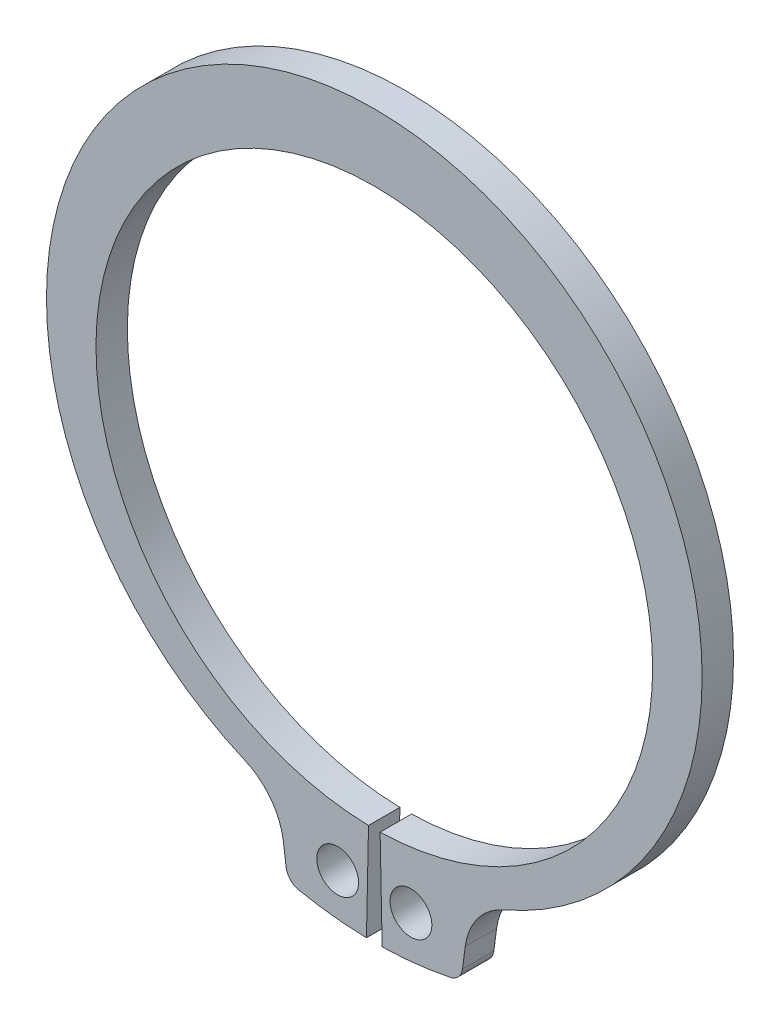
SolidWorks part; units mm, degrees
ref_plane "Plane1" through (0, 0, 0) normal (0, 0, 1) x (1, 0, 0)
ref_plane "Plane2" through (0, 0, 0) normal (0, 1, 0) x (1, 0, 0)
ref_plane "Plane3" through (0, 0, 0) normal (1, 0, 0) x (0, 0, -1)
sketch "Clipboard" plane through (0, 0, 0) normal (0, 0, 1) x (1, 0, 0)
  line L0 (0, 0) -> (3.2, 0)
  line L1 (0, 0) -> (0, 1.6)
  line L2 (0, 0) -> (0, -4.7)
  circle A0 centre (0, 0) radius 1
  circle A1 centre (0, 0) radius 14
  dimension "HoleDia" = 2
  dimension "ShaftDia" = 28
  dimension "LargeSection" = 3.2
  dimension "SmallSection" = 1.6
  dimension "LugSection" = 4.7
sketch "BodySke" plane through (0, 0, 0) normal (0, 0, 1) x (1, 0, 0)
  line L0 (-1.5431, 0) -> (1.5431, 0) construction
  line L1 (0, 0) -> (0, 16.5) construction
  line L2 (0.2771, -13.2971) -> (0.375, -17.9961)
  line L3 (-0.2771, -13.2971) -> (-0.375, -17.9961)
  line L4 (0, 0) -> (7.418, -16.4004) construction
  line L5 (0, 0) -> (-7.418, -16.4004) construction
  line L7 (4.3451, -15.9959) -> (4.2136, -16.9953)
  line L8 (-4.3451, -15.9959) -> (-4.2136, -16.9953)
  circle A0 centre (0, 0) radius 13.3 construction
  arc A1 (0.2771, -13.2971) -> (-0.2771, -13.2971) centre (0, 0) ccw
  arc A2 (6.1405, -13.5759) -> (-6.1405, -13.5759) centre (0, 0.8352) ccw construction
  arc A3 (0.375, -17.9961) -> (3.6208, -17.6321) centre (0, 0) ccw
  arc A4 (6.1927, -13.5535) -> (4.3451, -15.9959) centre (7.418, -16.4004) ccw
  arc A5 (-4.3451, -15.9959) -> (-6.1927, -13.5535) centre (-7.418, -16.4004) ccw
  arc A6 (-3.6208, -17.6321) -> (-0.375, -17.9961) centre (0, 0) ccw
  arc A7 (6.1927, -13.5535) -> (-6.1927, -13.5535) centre (0, 0.8352) ccw
  arc A8 (-4.4268, -15.3754) -> (4.4268, -15.3754) centre (0, 0) ccw construction
  circle A9 centre (1.75, -15.904) radius 1
  circle A10 centre (-1.75, -15.904) radius 1
  arc A11 (4.2136, -16.9953) -> (3.6208, -17.6321) centre (3.47, -16.8974) cw
  arc A12 (-4.2136, -16.9953) -> (-3.6208, -17.6321) centre (-3.47, -16.8974) ccw
  point P28 (4.145, -17.5163)
  point P31 (-4.145, -17.5163)
  dimension "HoleDia" = 2
  dimension "GrooveDia" = 26.6
  dimension "LugRad" = 18
  dimension "HoleOffsetRad" = 16
  dimension "D3" = 0.75
  dimension "LargeRad" = 16.5
  dimension "SmallRad" = 14.9
  dimension "SmallAngle" = 48.675
  dimension "D2" = 15
  dimension "HoleSpacing" = 3.5
  dimension "Gap" = 0.75
extrude "Body" add sketch "BodySke" against normal blind 1.5
sketch "NotSke" plane through (0, 0, 0) normal (0, 0, 1) x (1, 0, 0)
  line L0 (1.75, -14.904) -> (1.75, -16.904)
  line L1 (1.75, -16.904) -> (-1.75, -16.904)
  line L2 (-1.75, -16.904) -> (-1.75, -14.904)
  line L3 (-1.75, -14.904) -> (1.75, -14.904)
  circle A0 centre (1.75, -15.904) radius 1 construction
  circle A1 centre (-1.75, -15.904) radius 1 construction
extrude "Notch" [suppressed] cut sketch "NotSke" against normal through all
sketch "UnlSke" plane through (0, 0, 0) normal (0, 0, 1) x (1, 0, 0)
  line L0 (-3.0832, -17.734) -> (-2.2781, -13.1034)
  line L1 (3.0832, -17.734) -> (2.2781, -13.1034)
  arc A0 (2.2781, -13.1034) -> (-2.2781, -13.1034) centre (0, 0) ccw
  arc A1 (3.0832, -17.734) -> (-3.0832, -17.734) centre (0, 0) ccw
  arc A2 (0.375, -17.9961) -> (3.6208, -17.6321) centre (0, 0) ccw construction
  arc A3 (0.2771, -13.2971) -> (-0.2771, -13.2971) centre (0, 0) ccw construction
  circle A4 centre (-1.75, -15.904) radius 1 construction
  circle A5 centre (1.75, -15.904) radius 1 construction
extrude "Unlug" [suppressed] add sketch "UnlSke" against normal through all
equation "' \"ShaftDia@Clipboard\" = 3"
equation "' \"Thickness@Body\" = 0.4"
equation "' \"GrooveDia@BodySke\" = 2.8"
equation "' \"LugSection@Clipboard\" = 1.9"
equation "' \"LargeSection@Clipboard\" = 0.8"
equation "' \"HoleDia@Clipboard\" = 1.0"
equation "' \"ShaftDia@Clipboard\" = 10"
equation "' \"Thickness@Body\" = 1.0"
equation "' \"GrooveDia@BodySke\" = 9.6"
equation "' \"LugSection@Clipboard\" = 3.3"
equation "' \"LargeSection@Clipboard\" = 1.8"
equation "' \"HoleDia@Clipboard\" = 1.5"
equation "\"SmallSection@Clipboard\" = \"LargeSection@Clipboard\" * 0.5"
equation "\"Gap@BodySke\" =  \"Thickness@Body\" / 2"
equation "\"LargeRad@BodySke\" =  \"GrooveDia@BodySke\" / 2 +  \"LargeSection@Clipboard\""
equation "\"SmallRad@BodySke\" =  \"GrooveDia@BodySke\" / 2 +  \"SmallSection@Clipboard\""
equation "\"LugRad@BodySke\" = \"GrooveDia@BodySke\" / 2 + \"LugSection@Clipboard\""
equation "\"HoleOffsetRad@BodySke\" = (  \"ShaftDia@Clipboard\" / 2 + \"LugRad@BodySke\" ) / 2"
equation "\"HoleSpacing@BodySke\" = \"Gap@BodySke\"  * 2 +  \"HoleDia@Clipboard\""
equation "\"HoleDia@BodySke\" =  \"HoleDia@Clipboard\""
equation "\"SmallAngle@BodySke\" = atn(\"HoleSpacing@BodySke\" / 2 / sqr(\"HoleOffsetRad@BodySke\"  * \"HoleOffsetRad@BodySke\" - (\"HoleSpacing@BodySke\" / 2) * (\"HoleSpacing@BodySke\" / 2) ))  * 7 *  (\"LargeRad@BodySke\" / \"SmallRad@BodySke\")* ( 180 / 3.141593)"
